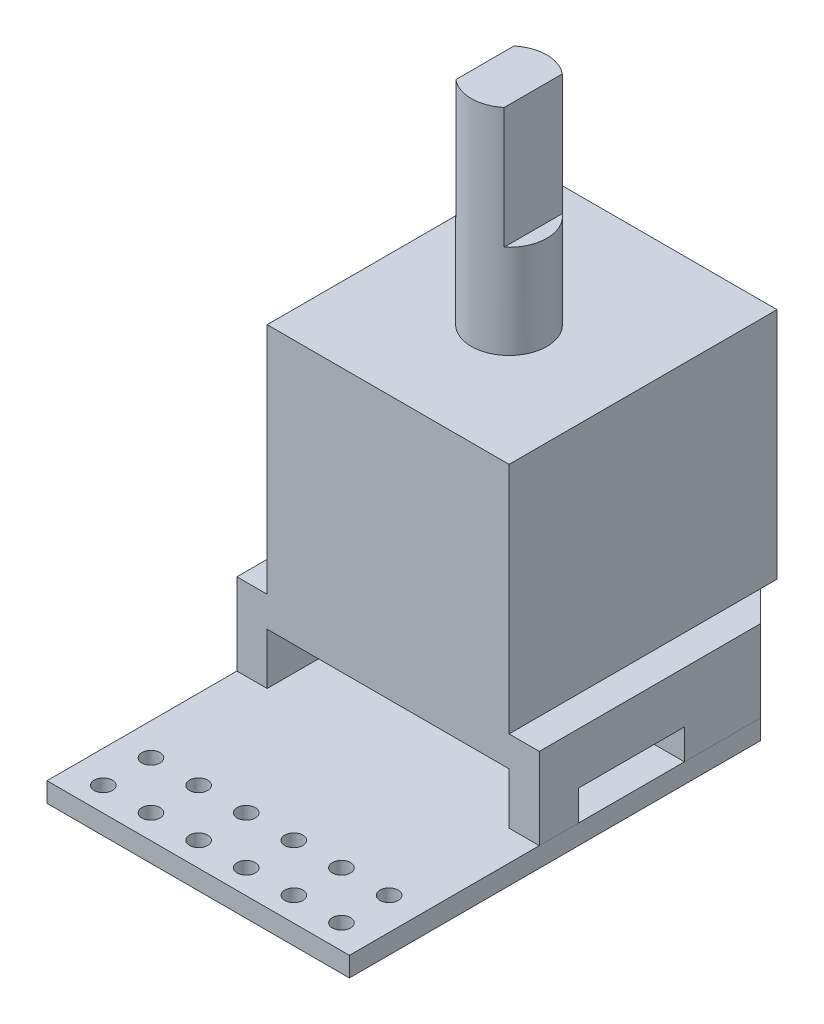
SolidWorks part; units mm, degrees
ref_plane "Front Plane" through (0, 0, 0) normal (0, 0, 1) x (1, 0, 0)
ref_plane "Top Plane" through (0, 0, 0) normal (0, 1, 0) x (1, 0, 0)
ref_plane "Right Plane" through (0, 0, 0) normal (1, 0, 0) x (0, 0, -1)
sketch "Sketch1" plane through (0, 0, 0) normal (0, 1, 0) x (1, 0, 0)
  line L0 (-55, 0) -> (55, 0) construction
  line L1 (-5.08, 5.6261) -> (5.08, 5.6261)
  line L2 (-5.08, 5.6261) -> (-5.08, -5.6261)
  line L3 (-5.08, -5.6261) -> (5.08, -5.6261)
  line L4 (5.08, 5.6261) -> (5.08, -5.6261)
  line L5 (0, -55) -> (0, 55) construction
  point P4 (5.08, 0)
  point P7 (0, 5.6261)
  dimension "D1" = 11.2522
  dimension "D2" = 10.16
extrude "Extrude1" add sketch "Sketch1" along normal blind 9.8044
sketch "Sketch2" plane through (0, 9.8044, 0) normal (0, 1, 0) x (1, 0, 0)
  line L1 (-5.08, -5.6261) -> (5.08, -5.6261) construction
  circle A0 centre (0, -0.5461) radius 1.5875
  dimension "D1" = 3.175
  dimension "D2" = 5.08
extrude "Extrude2" add sketch "Sketch2" along normal blind 9.017
sketch "Sketch3" plane through (0, 0, 0) normal (0, 0, 1) x (1, 0, 0)
  line L1 (-1.5875, 18.8214) -> (-1.016, 18.8214)
  line L2 (-1.5875, 18.8214) -> (-1.5875, 13.7414)
  line L3 (-1.5875, 13.7414) -> (-1.016, 13.7414)
  line L4 (-1.016, 18.8214) -> (-1.016, 13.7414)
  line L5 (1.5875, 18.8214) -> (1.016, 18.8214)
  line L6 (1.5875, 18.8214) -> (1.5875, 13.7414)
  line L7 (1.5875, 13.7414) -> (1.016, 13.7414)
  line L8 (1.016, 18.8214) -> (1.016, 13.7414)
  dimension "D1" = 2.032
  dimension "D2" = 5.08
extrude "Extrude3" cut sketch "Sketch3" against normal through all and the other way through all
sketch "Sketch4" plane through (0, 0, 0) normal (0, -1, 0) x (1, 0, 0)
  line L1 (-6.35, 5.6261) -> (6.35, 5.6261)
  line L2 (-6.35, 5.6261) -> (-6.35, -4.9403)
  line L3 (-6.35, -4.9403) -> (6.35, -4.9403)
  line L4 (6.35, 5.6261) -> (6.35, -4.9403)
  line L5 (0, -5.3924) -> (0, 5.3924) construction
  line L9 (-5.08, 5.6261) -> (5.08, 5.6261) construction
  point P4 (0, -4.9403)
  dimension "D1" = 12.7
  dimension "D2" = 10.5664
extrude "Extrude4" add sketch "Sketch4" along normal blind 3.429
sketch "Sketch5" plane through (0, 0, 5.6261) normal (0, 0, 1) x (1, 0, 0)
  line L0 (6.35, -3.429) -> (-6.35, -3.429) construction
  line L1 (-5.08, -3.429) -> (5.08, -3.429)
  line L2 (-5.08, -3.429) -> (-5.08, -1.27)
  line L3 (-5.08, -1.27) -> (5.08, -1.27)
  line L4 (5.08, -3.429) -> (5.08, -1.27)
  line L5 (0, -5.3924) -> (0, 5.3924) construction
  point P6 (0, -1.27)
  dimension "D1" = 10.16
  dimension "D2" = 2.159
extrude "Extrude5" cut sketch "Sketch5" against normal through all
sketch "Sketch6" plane through (6.35, 0, 0) normal (1, 0, 0) x (0, 0, -1)
  line L0 (4.9403, -3.429) -> (-5.6261, -3.429) construction
  line L1 (-3.9751, -3.429) -> (0.4699, -3.429)
  line L2 (-3.9751, -3.429) -> (-3.9751, -2.159)
  line L3 (-3.9751, -2.159) -> (0.4699, -2.159)
  line L4 (0.4699, -3.429) -> (0.4699, -2.159)
  line L5 (-5.6261, -3.429) -> (-5.6261, 0) construction
  dimension "D1" = 4.445
  dimension "D2" = 1.651
  dimension "D3" = 1.27
extrude "Extrude6" cut sketch "Sketch6" against normal up to surface (1.27 mm away) up to face at (5.08, -2.3495, 0.3429)
sketch "Sketch7" plane through (-6.35, 0, 0) normal (-1, 0, 0) x (0, 0, 1)
  line L0 (5.6261, -3.429) -> (-4.9403, -3.429) construction
  line L1 (1.0541, -3.429) -> (-4.9403, -3.429)
  line L2 (1.0541, -3.429) -> (1.0541, -2.159)
  line L3 (1.0541, -2.159) -> (-4.9403, -2.159)
  line L4 (-4.9403, -3.429) -> (-4.9403, -2.159)
  line L5 (5.6261, -3.429) -> (5.6261, 0) construction
  line L6 (-4.9403, -3.429) -> (-4.9403, 0) construction
  dimension "D1" = 4.572
  dimension "D2" = 1.27
extrude "Extrude7" cut sketch "Sketch7" against normal up to surface (1.27 mm away) up to face at (-5.08, -2.3495, 0.3429)
sketch "Sketch8" plane through (0, 0, 0) normal (0, 1, 0) x (1, 0, 0)
  line L0 (5.08, 4.9403) -> (6.35, 3.6703)
  line L1 (5.08, -5.6261) -> (5.08, 5.6261) construction
  line L2 (5.08, -5.6261) -> (5.08, 4.9403) construction
  line L3 (6.35, 4.9403) -> (6.35, -5.6261) construction
  line L4 (6.35, 3.6703) -> (6.35, 4.9403)
  line L5 (6.35, 4.9403) -> (6.35, 5.3848)
  line L6 (6.35, 5.3848) -> (-6.35, 5.3848)
  line L7 (-6.35, 5.3848) -> (-6.35, 3.6703)
  line L8 (-6.35, -5.6261) -> (-6.35, 4.9403) construction
  line L9 (-6.35, 3.6703) -> (-5.08, 4.9403)
  line L10 (-5.08, 4.9403) -> (5.08, 4.9403)
  line L11 (-5.08, 4.9403) -> (-5.08, -5.6261) construction
  dimension "D1" = 45
  dimension "D2" = 45
extrude "Extrude8" cut sketch "Sketch8" against normal up to surface (3.429 mm away) up to face at (5.715, -3.429, -2.7051)
sketch "Sketch9" plane through (0, -3.429, 0) normal (0, -1, 0) x (1, 0, 0)
  line L0 (5.08, -4.9403) -> (-5.08, -4.9403)
  line L1 (-5.08, -4.9403) -> (-6.35, -3.6703)
  line L2 (-6.35, -3.6703) -> (-6.35, 13.6017)
  line L3 (-6.35, 13.6017) -> (6.35, 13.6017)
  line L4 (6.35, 13.6017) -> (6.35, -3.6703)
  line L5 (6.35, -3.6703) -> (5.08, -4.9403)
  dimension "D1" = 17.272
extrude "PCB" add sketch "Sketch9" along normal blind 0.8255 separate body
sketch "Sketch10" plane through (0, -3.429, 0) normal (0, 1, 0) x (1, 0, 0)
  line L0 (6.35, -13.6017) -> (-6.35, -13.6017) construction
  circle A0 centre (-5, -12.5857) radius 0.381
  dimension "D1" = 5
  dimension "D2" = 1.016
  dimension "D3" = 0.762
extrude "Extrude10" cut sketch "Sketch10" against normal up to surface (0.8255 mm away) up to face at (0, -4.2545, 1.6637)
pattern_linear "LPattern1" count 6 spacing 2 along (1, 0, 0) count 2 spacing 2 along (0, 0, -1) of "Extrude10"
